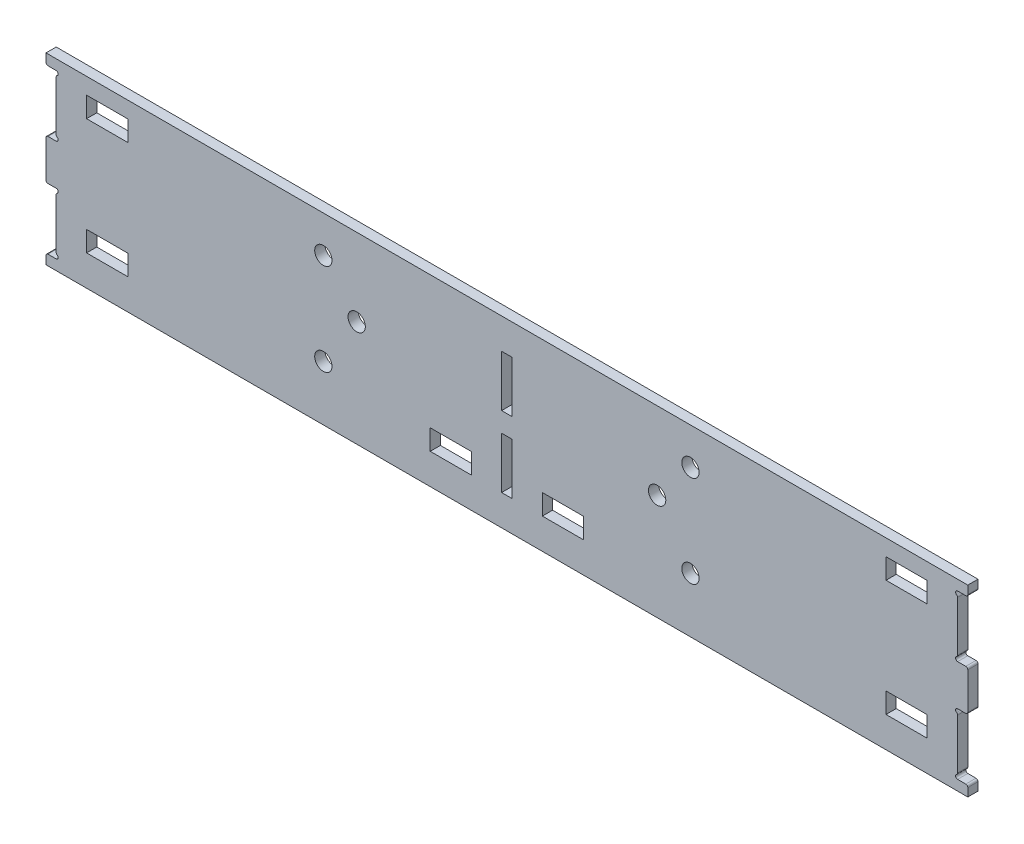
SolidWorks part; units mm, degrees
ref_plane "Front Plane" through (0, 0, 0) normal (0, 0, 1) x (1, 0, 0)
ref_plane "Top Plane" through (0, 0, 0) normal (0, 1, 0) x (1, 0, 0)
ref_plane "Right Plane" through (0, 0, 0) normal (1, 0, 0) x (0, 0, -1)
sketch "Sketch1" plane through (0, 0, 0) normal (0, 0, 1) x (1, 0, 0)
  line L1 (-226, -45) -> (226, -45)
  line L2 (-226, -45) -> (-226, 45)
  line L3 (-226, 45) -> (226, 45)
  line L4 (226, -45) -> (226, 45)
  line L5 (-226, -45) -> (226, 45) construction
  line L6 (-226, 45) -> (226, -45) construction
  point P0 (0, 0)
  dimension "D1" = 90
  dimension "D2" = 452
extrude "Boss-Extrude1" add sketch "Sketch1" along normal blind 5
sketch "Sketch2" plane through (0, 0, 5) normal (0, 0, 1) x (1, 0, 0)
  line L0 (226, 45) -> (-226, 45) construction
  line L1 (-2.6, 30) -> (2.6, 30)
  line L2 (-2.6, 30) -> (-2.6, 4.8)
  line L3 (-2.6, 4.8) -> (2.6, 4.8)
  line L4 (2.6, 30) -> (2.6, 4.8)
  line L5 (-2.6, -4.8) -> (2.6, -4.8)
  line L6 (-2.6, -4.8) -> (-2.6, -30)
  line L7 (-2.6, -30) -> (2.6, -30)
  line L8 (2.6, -4.8) -> (2.6, -30)
  line L9 (-226, -45) -> (226, -45) construction
  line L10 (0, -2.75) -> (0, 2.75) construction
  point P10 (0, -30)
  point P15 (0, -4.8)
  dimension "D1" = 15
  dimension "D2" = 25.2
  dimension "D3" = 25.2
  dimension "D4" = 15
  dimension "D5" = 0
  dimension "D6" = 5.2
extrude "Cut-Extrude1" cut sketch "Sketch2" against normal through all
sketch "Sketch3" plane through (0, 0, 5) normal (0, 0, 1) x (1, 0, 0)
  circle A8 centre (-77.6, 29) radius 1
  circle A9 centre (-72.4, 29) radius 1
  circle A10 centre (-77.6, 5.8) radius 1
  circle A11 centre (-72.4, 5.8) radius 1
  circle A24 centre (222.4, 29) radius 1
  circle A25 centre (227.6, 29) radius 1
  circle A26 centre (222.4, 5.8) radius 1
  circle A27 centre (227.6, 5.8) radius 1
  circle A28 centre (222.4, -5.8) radius 1
  circle A29 centre (227.6, -5.8) radius 1
  circle A30 centre (222.4, -29) radius 1
  circle A31 centre (227.6, -29) radius 1
sketch "Sketch4" plane through (-226, 0, 0) normal (-1, 0, 0) x (0, 0, 1)
  line L0 (0, 45) -> (0, -45) construction
  line L1 (0, 40) -> (5, 40)
  line L2 (0, 40) -> (0, 10)
  line L3 (0, 10) -> (5, 10)
  line L4 (5, 40) -> (5, 10)
  line L5 (5, 45) -> (5, -45) construction
  line L6 (5, -45) -> (0, -45) construction
  line L7 (0, -10) -> (5, -10)
  line L8 (0, -10) -> (0, -40)
  line L9 (0, -40) -> (5, -40)
  line L10 (5, -10) -> (5, -40)
  line L11 (5, 45) -> (0, 45) construction
  dimension "D1" = 5
  dimension "D2" = 30
  dimension "D3" = 30
  dimension "D4" = 5
extrude "Cut-Extrude5" cut sketch "Sketch4" against normal blind 5
mirror "Mirror2" about plane through (0, 0, 0) normal (1, 0, 0) of "Cut-Extrude5"
sketch "Sketch7" plane through (0, 0, 5) normal (0, 0, 1) x (1, 0, 0)
  line L0 (-221, 10) -> (-221, 40) construction
  line L1 (-221, -40) -> (-221, -10) construction
  line L2 (0, -2.75) -> (0, 2.75) construction
  circle A0 centre (-221, 39) radius 1
  circle A1 centre (-221, 11) radius 1
  circle A2 centre (-221, -11) radius 1
  circle A3 centre (-221, -39) radius 1
  circle A4 centre (221, -39) radius 1
  circle A5 centre (221, -11) radius 1
  circle A6 centre (221, 11) radius 1
  circle A7 centre (221, 39) radius 1
  dimension "D1" = 2
extrude "Cut-Extrude6" cut sketch "Sketch7" against normal through all
fillet "Fillet4" radius 1 16 edges at (-226, -40, 2.5) (-221, -38, 2.5) (-221, -12, 2.5) (-226, -10, 2.5) (-226, 10, 2.5) (-221, 12, 2.5) (-221, 38, 2.5) (-226, 40, 2.5) (226, -40, 2.5) (221, -38, 2.5) (221, -12, 2.5) (226, -10, 2.5) (226, 10, 2.5) (221, 12, 2.5) (221, 38, 2.5) (226, 40, 2.5)
extrude "Cut-Extrude7" cut sketch "Sketch8" against normal blind 10
sketch "Sketch8" plane through (0, -610.4562, 0) normal (0, 0, -1) x (-1, 0, 0)
  line L4 (-206.1, 590.4562) -> (-185.9, 590.4562)
  line L5 (-185.9, 590.4562) -> (-185.9, 580.4562)
  line L6 (-206.1, 580.4562) -> (-185.9, 580.4562)
  line L7 (-206.1, 590.4562) -> (-206.1, 580.4562)
  line L40 (-221, 570.4562) -> (-225, 570.4562)
  line L41 (-226, 569.4562) -> (-226, 565.4562)
  line L42 (-226, 565.4562) -> (226, 565.4562)
  line L43 (226, 565.4562) -> (226, 569.4562)
  line L44 (225, 570.4562) -> (221, 570.4562)
  line L45 (221, 573.1882) -> (221, 597.7241)
  line L46 (221, 600.4562) -> (225, 600.4562)
  line L47 (226, 601.4562) -> (226, 619.4562)
  line L48 (225, 620.4562) -> (221, 620.4562)
  line L49 (221, 623.1882) -> (221, 647.7241)
  line L50 (221, 650.4562) -> (225, 650.4562)
  line L51 (226, 651.4562) -> (226, 655.4562)
  line L52 (226, 655.4562) -> (-226, 655.4562)
  line L53 (-226, 655.4562) -> (-226, 651.4562)
  line L54 (-225, 650.4562) -> (-221, 650.4562)
  line L55 (-221, 647.7241) -> (-221, 623.1882)
  line L56 (-221, 620.4562) -> (-225, 620.4562)
  line L57 (-226, 619.4562) -> (-226, 601.4562)
  line L58 (-225, 600.4562) -> (-221, 600.4562)
  line L59 (-221, 597.7241) -> (-221, 573.1882)
  arc A48 (-225, 570.4562) -> (-226, 569.4562) centre (-225, 569.4562) ccw
  arc A49 (226, 569.4562) -> (225, 570.4562) centre (225, 569.4562) ccw
  arc A50 (220.5, 572.3222) -> (221, 570.4562) centre (221, 571.4562) ccw
  arc A51 (220.5, 572.3222) -> (221, 573.1882) centre (220, 573.1882) ccw
  arc A52 (221, 597.7241) -> (220.5, 598.5901) centre (220, 597.7241) ccw
  arc A53 (221, 600.4562) -> (220.5, 598.5901) centre (221, 599.4562) ccw
  arc A54 (225, 600.4562) -> (226, 601.4562) centre (225, 601.4562) ccw
  arc A55 (226, 619.4562) -> (225, 620.4562) centre (225, 619.4562) ccw
  arc A56 (220.5, 622.3222) -> (221, 620.4562) centre (221, 621.4562) ccw
  arc A57 (220.5, 622.3222) -> (221, 623.1882) centre (220, 623.1882) ccw
  arc A58 (221, 647.7241) -> (220.5, 648.5901) centre (220, 647.7241) ccw
  arc A59 (221, 650.4562) -> (220.5, 648.5901) centre (221, 649.4562) ccw
  arc A60 (225, 650.4562) -> (226, 651.4562) centre (225, 651.4562) ccw
  arc A61 (-226, 651.4562) -> (-225, 650.4562) centre (-225, 651.4562) ccw
  arc A62 (-220.5, 648.5901) -> (-221, 650.4562) centre (-221, 649.4562) ccw
  arc A63 (-220.5, 648.5901) -> (-221, 647.7241) centre (-220, 647.7241) ccw
  arc A64 (-221, 623.1882) -> (-220.5, 622.3222) centre (-220, 623.1882) ccw
  arc A65 (-221, 620.4562) -> (-220.5, 622.3222) centre (-221, 621.4562) ccw
  arc A66 (-225, 620.4562) -> (-226, 619.4562) centre (-225, 619.4562) ccw
  arc A67 (-226, 601.4562) -> (-225, 600.4562) centre (-225, 601.4562) ccw
  arc A68 (-220.5, 598.5901) -> (-221, 600.4562) centre (-221, 599.4562) ccw
  arc A69 (-220.5, 598.5901) -> (-221, 597.7241) centre (-220, 597.7241) ccw
  arc A70 (-221, 573.1882) -> (-220.5, 572.3222) centre (-220, 573.1882) ccw
  arc A71 (-221, 570.4562) -> (-220.5, 572.3222) centre (-221, 571.4562) ccw
mirror "Mirror3" about plane through (0, 0, 0) normal (1, 0, 0) of "Cut-Extrude7"
extrude "Cut-Extrude8" cut sketch "Sketch9" against normal blind 300
sketch "Sketch9" plane through (0, -610.4562, -223.6) normal (0, 0, -1) x (-1, 0, 0)
  line L4 (17.4, 590.4562) -> (37.6, 590.4562)
  line L5 (37.6, 590.4562) -> (37.6, 580.4562)
  line L6 (17.4, 580.4562) -> (37.6, 580.4562)
  line L7 (17.4, 590.4562) -> (17.4, 580.4562)
mirror "Mirror4" about plane through (0, 0, 0) normal (1, 0, 0) of "Cut-Extrude8"
ref_plane "Plane1" through (0, 3.5, 0) normal (0, 1, 0) x (1, 0, 0)
mirror "Mirror5" about plane through (0, 3.5, 0) normal (0, 1, 0) of "Mirror3", "Cut-Extrude7"
extrude "Cut-Extrude10" cut sketch "Sketch11" against normal blind 20
sketch "Sketch11" plane through (-635.0724, 447.1656, -5) normal (0, 0, -1) x (1, 0, 0)
  circle A2 centre (545.0724, 420.1656) radius 4.25
  circle A3 centre (545.0724, 465.1656) radius 4.25
  dimension "D1" = 8.5
mirror "Mirror6" about plane through (0, 0, 0) normal (1, 0, 0) of "Cut-Extrude10"
extrude "Cut-Extrude11" cut sketch "Sketch12" against normal blind 600 and the other way blind 30
sketch "Sketch12" plane through (537.5236, -819.4771, 0) normal (0, 0, -1) x (-1, 0, 0)
  line L1 (537.5236, 936.4771) -> (537.5236, 56.4771) construction
  circle A0 centre (611.1815, 826.4771) radius 4.25
  circle A1 centre (463.8658, 826.4771) radius 4.25
